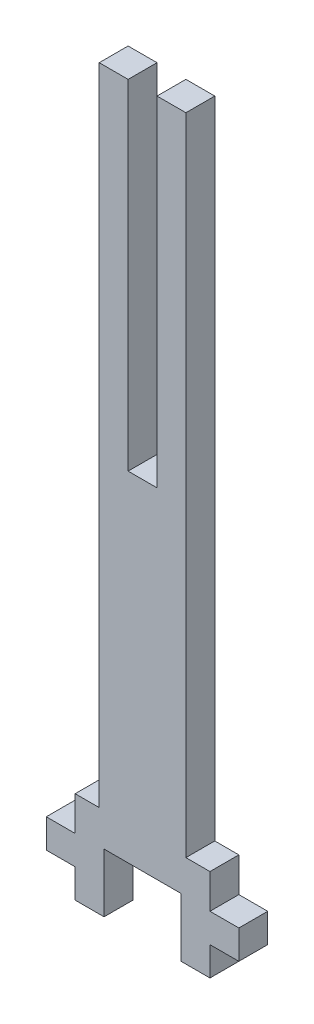
SolidWorks part; units mm, degrees
ref_plane "Front Plane" through (0, 0, 0) normal (0, 0, 1) x (1, 0, 0)
ref_plane "Top Plane" through (0, 0, 0) normal (0, 1, 0) x (1, 0, 0)
ref_plane "Right Plane" through (0, 0, 0) normal (1, 0, 0) x (0, 0, -1)
sketch "스케치1" plane through (0, 0, 0) normal (0, 0, 1) x (1, 0, 0)
  line L0 (0, 0) -> (0, -32.1835) construction
  line L1 (-7, -38.2835) -> (7, -38.2835) construction
  line L2 (-7, -38.2835) -> (-7, 38.2835) construction
  line L3 (-7, 38.2835) -> (7, 38.2835) construction
  line L4 (7, -38.2835) -> (7, 38.2835) construction
  line L5 (-7, -38.2835) -> (7, 38.2835) construction
  line L6 (-7, 38.2835) -> (7, -38.2835) construction
  line L7 (-4, -38.2835) -> (4, -38.2835) construction
  line L8 (-4, -38.2835) -> (-4, -32.1835)
  line L9 (-4, -32.1835) -> (4, -32.1835)
  line L10 (4, -38.2835) -> (4, -32.1835)
  line L11 (-4, -38.2835) -> (4, -32.1835) construction
  line L12 (-4, -32.1835) -> (4, -38.2835) construction
  line L13 (4.5, -28.7085) -> (-4.5, -28.7085) construction
  line L14 (7, -28.7085) -> (4.5, -28.7085)
  line L15 (7, -28.7085) -> (7, 38.2835) construction
  line L16 (7, 38.2835) -> (4.5, 38.2835) construction
  line L17 (4.5, -28.7085) -> (4.5, 38.2835) construction
  line L18 (7, -28.7085) -> (4.5, 38.2835) construction
  line L19 (7, 38.2835) -> (4.5, -28.7085) construction
  line L20 (-4.5, 38.2835) -> (-7, 38.2835) construction
  line L21 (-4.5, 38.2835) -> (-4.5, -28.7085) construction
  line L22 (-4.5, -28.7085) -> (-7, -28.7085)
  line L23 (-7, 38.2835) -> (-7, -28.7085) construction
  line L24 (-4.5, 38.2835) -> (-7, -28.7085) construction
  line L25 (-4.5, -28.7085) -> (-7, 38.2835) construction
  line L26 (4, -38.2835) -> (7, -38.2835)
  line L27 (-1.5, 28.7085) -> (1.5, 28.7085) construction
  line L28 (-1.5, 28.7085) -> (-1.5, -28.7085) construction
  line L29 (-1.5, -28.7085) -> (1.5, -28.7085) construction
  line L30 (1.5, 28.7085) -> (1.5, -28.7085) construction
  line L31 (-1.5, 28.7085) -> (1.5, -28.7085) construction
  line L32 (-1.5, -28.7085) -> (1.5, 28.7085) construction
  line L33 (7, -38.2835) -> (7, -28.7085)
  line L34 (-7, -28.7085) -> (-7, -38.2835)
  line L35 (-7, -38.2835) -> (-4, -38.2835)
  line L36 (-4.5, 38.2835) -> (-7, 38.2835) construction
  line L37 (-7, 38.2835) -> (-7, -38.2835)
  line L38 (4.5, 38.2835) -> (7, 38.2835) construction
  line L39 (-4.5, -28.7085) -> (-4.5, 38.2835)
  line L40 (4.5, 38.2835) -> (4.5, -28.7085)
  line L41 (-4.5, 38.2835) -> (4.5, 38.2835)
  point P0 (0, 0)
  point P10 (0, -35.2335)
  point P16 (5.75, 4.7875)
  point P20 (-5.75, 4.7875)
  dimension "D1" = 66.992
  dimension "D2" = 3
  dimension "D3" = 8
  dimension "D4" = 6.1
  dimension "D5" = 3
  dimension "D6" = 3.475
  dimension "D7" = 3
extrude "보스-돌출1" add sketch "스케치1" along normal blind 3 contours L41 L39 L22 L34 L35 L8 L9 L10 L26 L33 L14 L40
sketch "스케치2" plane through (0, 0, 3) normal (0, 0, 1) x (1, 0, 0)
  line L0 (0, 38.2835) -> (0, -32.1835) construction
  line L1 (-4.5, 38.2835) -> (4.5, 38.2835) construction
  line L2 (-4, -32.1835) -> (4, -32.1835) construction
  line L4 (-1.5, 38.2835) -> (1.5, 38.2835)
  line L5 (-1.5, 38.2835) -> (-1.5, 3.05)
  line L6 (-1.5, 3.05) -> (1.5, 3.05)
  line L7 (1.5, 38.2835) -> (1.5, 3.05)
  line L8 (-1.5, 38.2835) -> (1.5, 3.05) construction
  line L9 (-1.5, 3.05) -> (1.5, 38.2835) construction
  point P6 (0, 3.05)
  point P7 (0, 20.6668)
  dimension "D1" = 3
extrude "컷-돌출1" cut sketch "스케치2" against normal up to surface (3 mm away) up to face at (0, -21.314, 0)
sketch "스케치3" plane through (0, 0, 3) normal (0, 0, 1) x (1, 0, 0)
  line L0 (-7, -38.2835) -> (-4, -38.2835) construction
  line L1 (-7, -35.2835) -> (-10, -35.2835)
  line L2 (-7, -35.2835) -> (-7, -32.2835)
  line L3 (-7, -32.2835) -> (-10, -32.2835)
  line L4 (-10, -35.2835) -> (-10, -32.2835)
  line L5 (-7, -35.2835) -> (-10, -32.2835) construction
  line L6 (-7, -32.2835) -> (-10, -35.2835) construction
  line L7 (7, -35.2835) -> (10, -35.2835)
  line L8 (7, -35.2835) -> (7, -32.2835)
  line L9 (7, -32.2835) -> (10, -32.2835)
  line L10 (10, -35.2835) -> (10, -32.2835)
  line L11 (7, -35.2835) -> (10, -32.2835) construction
  line L12 (7, -32.2835) -> (10, -35.2835) construction
  line L13 (7, -38.2835) -> (7, -28.7085) construction
  line L14 (-7, -28.7085) -> (-7, -38.2835) construction
  point P4 (-8.5, -33.7835)
  point P10 (8.5, -33.7835)
  dimension "D1" = 3
  dimension "D2" = 3
  dimension "D3" = 3
  dimension "D4" = 3
  dimension "D5" = 3
  dimension "D6" = 3
extrude "보스-돌출2" add sketch "스케치3" against normal blind 3
